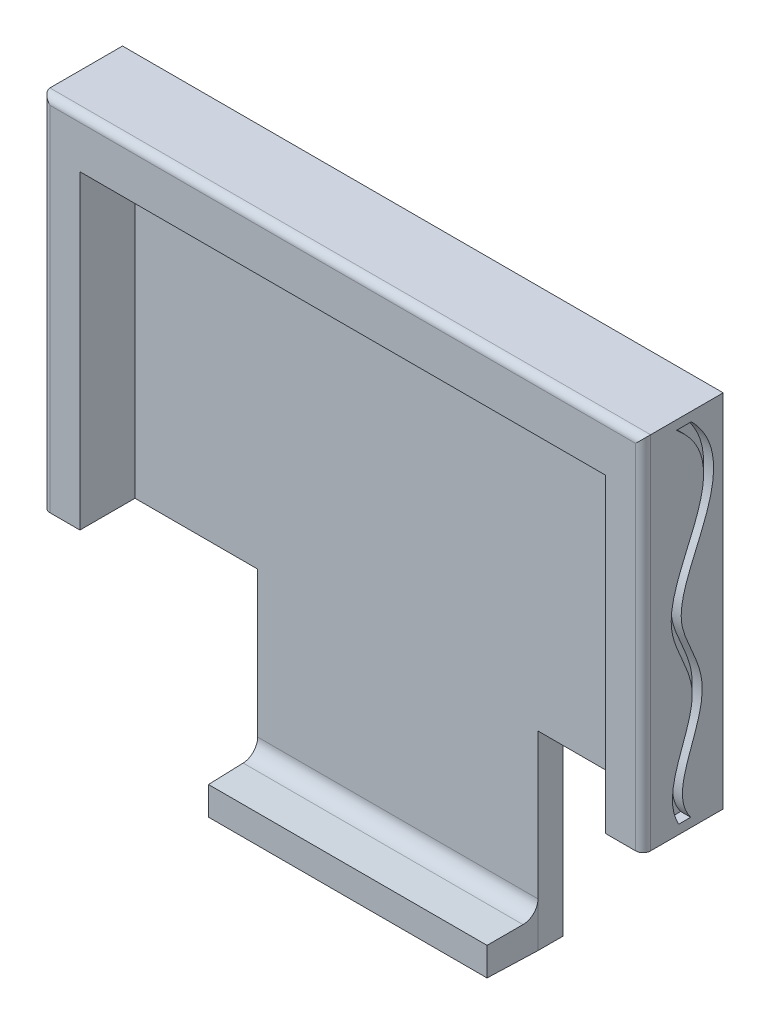
SolidWorks part; units mm, degrees
ref_plane "Plano frontal" through (0, 0, 0) normal (0, 0, 1) x (1, 0, 0)
ref_plane "Plano superior" through (0, 0, 0) normal (0, 1, 0) x (1, 0, 0)
ref_plane "Plano direito" through (0, 0, 0) normal (1, 0, 0) x (0, 0, -1)
sketch "Esboço1" plane through (0, 0, 0) normal (0, 0, 1) x (1, 0, 0)
  line L1 (0, 0) -> (120, 0)
  line L2 (0, 0) -> (0, 110)
  line L3 (0, 110) -> (120, 110)
  line L4 (120, 0) -> (120, 110)
  dimension "D1" = 120
  dimension "D2" = 110
extrude "Ressalto-extrusão1" add sketch "Esboço1" along normal blind 16
sketch "Esboço2" plane through (0, 0, 16) normal (0, 0, 1) x (1, 0, 0)
  line L0 (0, 0) -> (120, 0) construction
  line L1 (7.5, 0) -> (112.5, 0)
  line L2 (7.5, 0) -> (7.5, 100)
  line L3 (7.5, 100) -> (112.5, 100)
  line L4 (112.5, 0) -> (112.5, 100)
  line L5 (60, 110) -> (60, 0) construction
  line L6 (120, 110) -> (0, 110) construction
  point P10 (60, 100)
  dimension "D1" = 105
  dimension "D2" = 100
extrude "Corte-extrusão1" cut sketch "Esboço2" against normal blind 11
sketch "Esboço3" plane through (0, 0, 5) normal (0, 0, 1) x (1, 0, 0)
  line L0 (60, 110) -> (60, 0) construction
  line L1 (0, 0) -> (32, 0)
  line L2 (0, 0) -> (0, 38)
  line L3 (0, 38) -> (32, 38)
  line L4 (32, 0) -> (32, 38)
  line L5 (120, 110) -> (0, 110) construction
  line L6 (7.5, 0) -> (112.5, 0) construction
  line L7 (120, 0) -> (120, 38)
  line L8 (120, 0) -> (88, 0)
  line L9 (88, 0) -> (88, 38)
  line L10 (120, 38) -> (88, 38)
  dimension "D1" = 38
  dimension "D2" = 32
  dimension "D3" = 72
extrude "Corte-extrusão2" cut sketch "Esboço3" along normal through all both and the other way through all
sketch "Esboço4" plane through (0, 0, 5) normal (0, 0, 1) x (1, 0, 0)
  line L0 (32, 0) -> (88, 0)
  line L4 (32, 0) -> (32, 6)
  line L5 (32, 0) -> (32, 38) construction
  line L6 (32, 6) -> (88, 6)
  line L7 (88, 38) -> (88, 0) construction
  line L8 (88, 6) -> (88, 0)
  dimension "D1" = 6
extrude "Ressalto-extrusão2" add sketch "Esboço4" along normal blind 10 draft 1 from surface at 0 starting at face at (60, 44, 5)
ref_plane "Plano1" through (0, 110, 0) normal (-1, 0, 0) x (0, 0, 1)
sketch "Esboço6" plane through (0, 0, 0) normal (-1, 0, 0) x (0, 0, 1)
  line L2 (13.1861, 100) -> (2.2049, 107.1603)
  line L8 (5, 100) -> (16, 100) construction
  line L9 (2.2049, 107.1603) -> (2.2049, 101.9565)
  line L10 (2.2049, 101.9565) -> (5.0322, 96.343)
  line L11 (5.0322, 96.343) -> (13.1861, 100)
extrude "Corte-extrusão3" cut sketch "Esboço6" against normal blind 105 from surface at -7.5 starting at face at (7.5, 69, 10.5)
sketch "Esboço8" plane through (120, 0, 0) normal (1, 0, 0) x (0, 0, -1)
  line L0 (-16, 110) -> (0, 110) construction
  line L1 (-16, 38) -> (0, 38) construction
  line L2 (-11.7923, 110) -> (-10.6901, 111.6689)
  line L3 (-6.0825, 39.2765) -> (-4.1496, 38)
  line L4 (-4.1496, 38) -> (-7.6221, 38)
  spline S0 degree 3 poles (-7.6221, 38) (-14.2905, 46.0432) (-0.8935, 58.3952) (-18.324, 81.192) (5.9288, 98.2966) (-11.7923, 110) knots 0 0 0 0 0.328017 0.501208 1 1 1 1
  spline S1 degree 1 poles (-6.0825, 39.2765) (-10.6901, 111.6689) knots 0 0 1 1 construction
  spline S2 degree 3 poles (-6.0825, 39.2765) (-6.2142, 39.4354) (-6.4743, 39.7672) (-6.9156, 40.4029) (-7.36, 41.1854) (-7.7382, 42.1007) (-8.0694, 43.3118) (-8.2015, 44.8469) (-7.9847, 46.8057) (-7.4563, 48.8855) (-6.4657, 51.7918) (-5.2723, 54.8569) (-4.4179, 58.1096) (-4.0993, 60.665) (-4.356, 63.3535) (-5.1078, 65.7988) (-6.0605, 68.0857) (-7.0315, 70.2392) (-7.843, 72.2767) (-8.3377, 74.136) (-8.4386, 75.9276) (-8.1421, 78.5087) (-7.0374, 81.9966) (-5.0573, 86.4909) (-3.0686, 91.2139) (-1.976, 95.3848) (-1.8671, 98.8908) (-2.2949, 101.5751) (-3.3331, 104.2469) (-4.7502, 106.4028) (-6.2303, 108.0717) (-7.5178, 109.2959) (-8.747, 110.2966) (-9.8213, 111.0823) (-10.4011, 111.478) (-10.6901, 111.6689) knots 0 0 0 0 0.007812 0.015625 0.03125 0.046875 0.0625 0.09375 0.125 0.15625 0.1875 0.25 0.28125 0.3125 0.34375 0.375 0.40625 0.4375 0.46875 0.5 0.53125 0.5625 0.625 0.6875 0.75 0.8125 0.84375 0.875 0.90625 0.9375 0.953125 0.96875 0.984375 0.992188 1 1 1 1
  point P2 (-8.0755, 52.071)
  dimension "D1" = 2
extrude "Corte-extrusão5" cut sketch "Esboço8" against normal blind 2 and the other way through all
sketch "Esboço9" plane through (0, 0, 16) normal (0, 0, 1) x (1, 0, 0)
  line L0 (60, 110) -> (60, 0) construction
  line L1 (0, 110) -> (3.9897, 110)
  line L2 (0, 110) -> (0, 108.1807)
  line L3 (0, 108.1807) -> (3.9897, 108.1807)
  line L4 (3.9897, 110) -> (3.9897, 108.1807)
  line L5 (120, 110) -> (0, 110) construction
  line L6 (120, 108.1807) -> (116.0103, 108.1807)
  line L7 (116.0103, 110) -> (116.0103, 108.1807)
  line L8 (120, 110) -> (116.0103, 110)
  line L9 (120, 110) -> (120, 108.1807)
  line L10 (0, 74) -> (120, 74) construction
  line L11 (0, 110) -> (0, 38) construction
  line L12 (120, 38) -> (120, 110) construction
  line L13 (0, 39.8193) -> (3.9897, 39.8193)
  line L14 (3.9897, 38) -> (3.9897, 39.8193)
  line L15 (0, 38) -> (3.9897, 38)
  line L16 (0, 38) -> (0, 39.8193)
  line L17 (120, 38) -> (120, 39.8193)
  line L18 (116.0103, 38) -> (116.0103, 39.8193)
  line L19 (120, 39.8193) -> (116.0103, 39.8193)
  line L20 (120, 38) -> (116.0103, 38)
  dimension "D1" = 1.8193
  dimension "D2" = 3.9897
extrude "Ressalto-extrusão3" add sketch "Esboço9" against normal blind 16
sketch "Esboço11" plane through (0, 0, 16) normal (0, 0, 1) x (1, 0, 0)
  line L0 (120, 110) -> (0, 110) construction
  line L1 (7.5, 28) -> (1.9962, 28)
  line L2 (7.5, 28) -> (7.5, 110)
  line L3 (7.5, 110) -> (1.9962, 110)
  line L4 (1.9962, 28) -> (1.9962, 110)
  line L5 (60, 110) -> (60, -5.8254) construction
  line L7 (112.5, 110) -> (118.0038, 110)
  line L8 (118.0038, 28) -> (118.0038, 110)
  line L9 (112.5, 28) -> (118.0038, 28)
  line L10 (112.5, 28) -> (112.5, 110)
extrude "Ressalto-extrusão4" add sketch "Esboço11" against normal blind 16
sketch "Esboço15" plane through (112.5, 0, 0) normal (-1, 0, 0) x (0, 0, 1)
  line L0 (5.9829, 104.6968) -> (8.5829, 103.0015)
  line L1 (8.5829, 103.0015) -> (11.7923, 110)
  line L2 (11.7923, 110) -> (8.4162, 110)
  line L3 (8.4162, 110) -> (2.7952, 106.7754)
  line L5 (2.7952, 106.7754) -> (5.9829, 104.6968)
  line L8 (13.1861, 100) -> (2.2049, 107.1603) construction
  point P2 (7.5028, 102.4467)
  point P3 (7.9523, 102.9122)
  point P4 (8.5829, 103.0015)
  point P12 (2.7952, 106.7754)
  point P13 (3.2914, 107.1075)
extrude "Ressalto-extrusão7" add sketch "Esboço15" along normal blind 107
ref_plane "Plano2" through (60, 0, 0) normal (1, 0, 0) x (0, 0, -1)
mirror "Espelhar1" about plane through (60, 0, 0) normal (1, 0, 0) of "Corte-extrusão5"
sketch "Esboço16" plane through (0, 0, 16) normal (0, 0, 1) x (1, 0, 0)
  line L0 (0, 110) -> (3.99, 110)
  line L1 (120, 110) -> (0, 110) construction
  line L2 (3.99, 110) -> (3.99, 108.18)
  line L3 (3.99, 108.18) -> (0, 108.18)
  line L4 (0, 110) -> (0, 38) construction
  line L5 (0, 108.18) -> (0, 110)
  line L6 (0, 74) -> (120, 74) construction
  line L7 (120, 38) -> (120, 110) construction
  line L8 (3.99, 39.82) -> (0, 39.82)
  line L9 (3.99, 38) -> (3.99, 39.82)
  line L10 (0, 38) -> (3.99, 38)
  line L11 (0, 39.82) -> (0, 38)
  dimension "D1" = 1.82
  dimension "D2" = 3.99
extrude "Ressalto-extrusão8" add sketch "Esboço16" against normal through all
sketch "Esboço17" plane through (0, 0, 16) normal (0, 0, 1) x (1, 0, 0)
  line L1 (1.9962, 38) -> (7.5, 38)
  line L2 (1.9962, 38) -> (1.9962, 28)
  line L3 (1.9962, 28) -> (7.5, 28)
  line L4 (7.5, 38) -> (7.5, 28)
  line L5 (112.5, 28) -> (118.0038, 28)
  line L6 (112.5, 28) -> (112.5, 38)
  line L7 (112.5, 38) -> (118.0038, 38)
  line L8 (118.0038, 28) -> (118.0038, 38)
extrude "Corte-extrusão6" cut sketch "Esboço17" against normal through all
fillet "Filete2" radius 1.5 3 edges at (120, 74, 16) (0, 74, 16) (60, 110, 16)
sketch "Esboço19" plane through (0, -0.0872, 0.0015) normal (0, -0.9998, 0.0175) x (1, 0, 0)
  line L0 (32.0166, 5.9531) -> (87.9834, 5.9531) construction
  line L1 (32.1746, 15.0008) -> (32, 4.9992) construction
  line L2 (87.8254, 15.0008) -> (88, 4.9992) construction
  text T0 "PHX" font "Impact" height 7
extrude "Corte-extrusão7" cut sketch "Esboço19" against normal blind 2
fillet "Filete3" radius 3 1 edges at (60, 6, 5)
